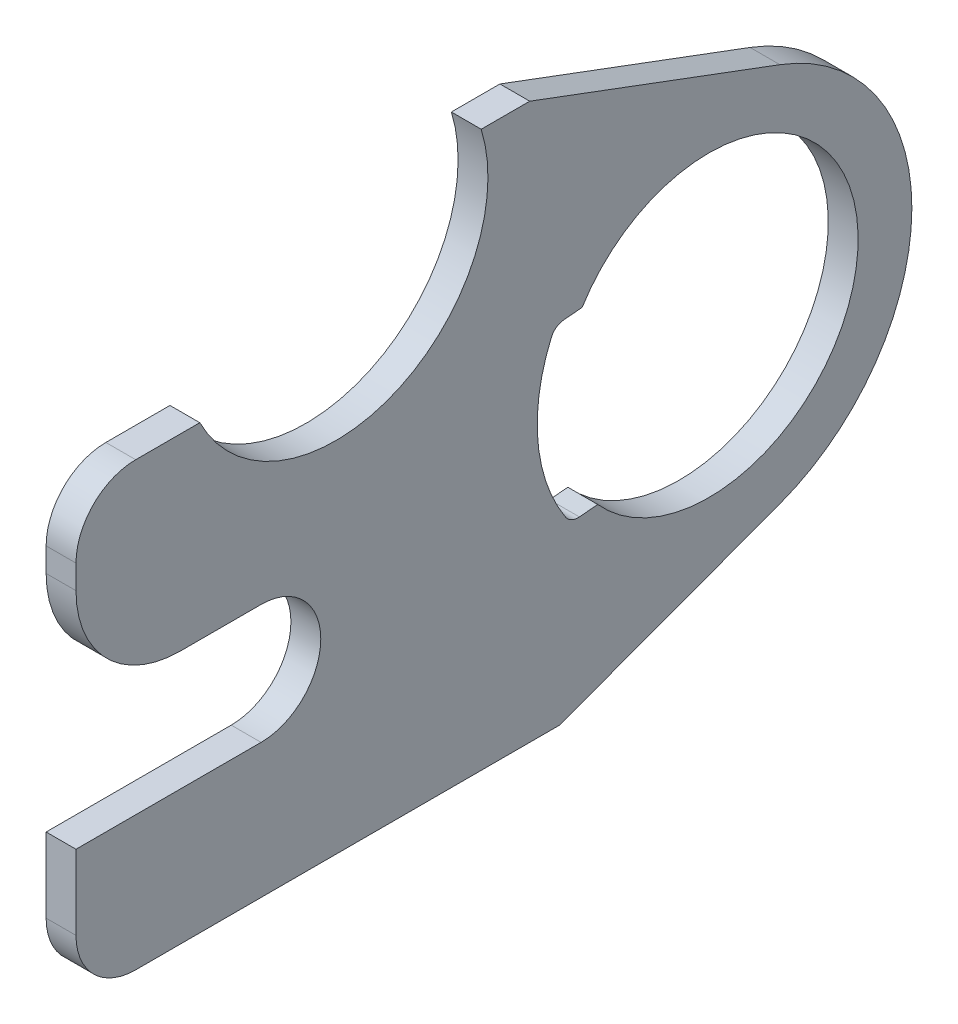
SolidWorks part; units mm, degrees
material "Q355"
ref_plane "前视基准面" through (0, 0, 0) normal (0, 0, 1) x (1, 0, 0)
ref_plane "上视基准面" through (0, 0, 0) normal (0, 1, 0) x (1, 0, 0)
ref_plane "右视基准面" through (0, 0, 0) normal (1, 0, 0) x (0, 0, -1)
sketch "草图1" plane through (0, 0, 0) normal (1, 0, 0) x (0, 0, -1)
  line L0 (-212, -91) -> (-50, -91)
  line L1 (-50, -91) -> (23.5925, -63.7761)
  line L2 (-60, 95) -> (-76.2558, 95)
  line L3 (-60, 95) -> (23.7937, 63.7013)
  line L4 (-212, -91) -> (-212, -46)
  line L5 (-212, -46) -> (-150, -46)
  line L6 (-150, -6) -> (-212, -6)
  line L8 (-212, -6) -> (-212, 57)
  line L9 (-212, 57) -> (-170.5192, 57)
  circle A0 centre (0, 0) radius 50
  arc A1 (-170.5192, 57) -> (-76.2558, 95) centre (-125, 80) ccw
  arc A2 (23.5925, -63.7761) -> (23.7937, 63.7013) centre (0, 0) ccw
  arc A3 (-150, -46) -> (-150, -6) centre (-150, -26) ccw
  dimension "D1" = 80
  dimension "D2" = 125
  dimension "D3" = 100
  dimension "D4" = 212
  dimension "D5" = 95
  dimension "D6" = 91
  dimension "D7" = 68
  dimension "D8" = 20
  dimension "D9" = 62
  dimension "D10" = 65
  dimension "D11" = 102
  dimension "D12" = 83
  dimension "D13" = 60
  dimension "D14" = 50
extrude "凸台-拉伸1" add sketch "草图1" along normal blind 10
fillet "圆角1" radius 20 2 edges at (5, -91, 212) (5, 57, 212)
fillet "圆角2" radius 35 1 edges at (5, -6, 212)
sketch "草图2" plane through (10, 0, 0) normal (1, 0, 0) x (0, 0, -1)
  line L0 (0, 0) -> (-57.2812, -5.0115) construction
  line L1 (-42.4625, 26.3996) -> (-51.4816, 25.6105)
  line L2 (-37.2331, -33.3721) -> (-46.2522, -34.1611)
  line L3 (-2.6147, 29.8858) -> (-59.8959, 24.8744) construction
  line L4 (2.6147, -29.8858) -> (-54.6665, -34.8973) construction
  line L5 (0, 0) -> (0, 50) construction
  arc A0 (-51.4816, 25.6105) -> (-46.2522, -34.1611) centre (0, 0) ccw
  circle A1 centre (0, 0) radius 50 construction
  arc A2 (-42.4625, 26.3996) -> (-37.2331, -33.3721) centre (0, 0) ccw
  dimension "D1" = 115
  dimension "D4" = 95
  dimension "D2" = 30
  dimension "D3" = 30
extrude "切除-拉伸1" cut sketch "草图2" against normal blind 12
fillet "圆角3" radius 5 2 edges at (5, -34.1611, 46.2522) (5, 25.6105, 51.4816)
